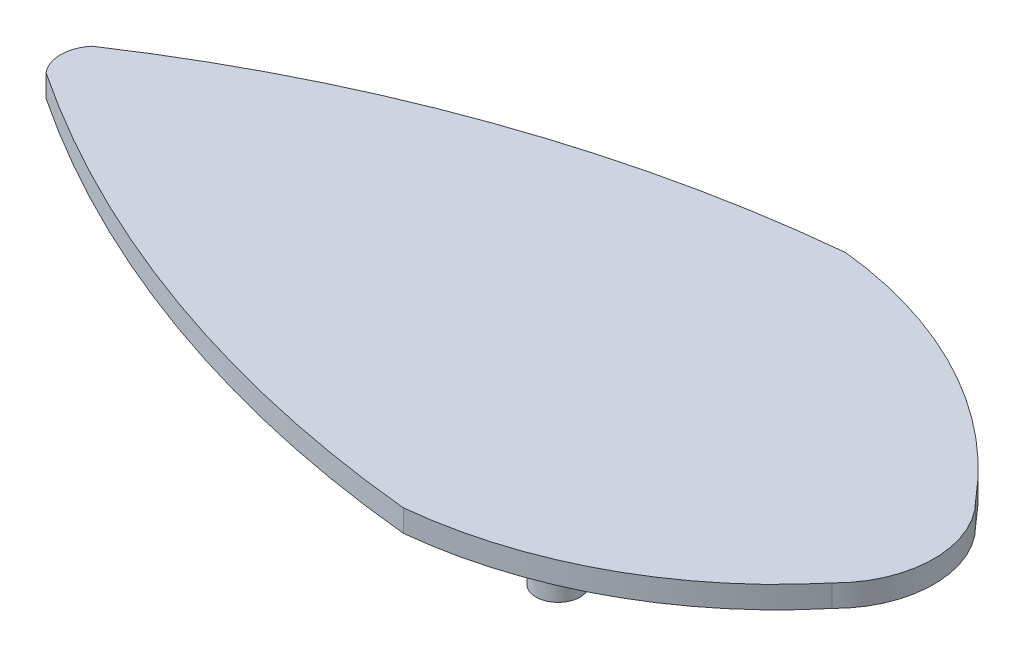
SolidWorks part; units mm, degrees
ref_plane "Alzado" through (0, 0, 0) normal (0, 0, 1) x (1, 0, 0)
ref_plane "Planta" through (0, 0, 0) normal (0, 1, 0) x (1, 0, 0)
ref_plane "Vista lateral" through (0, 0, 0) normal (1, 0, 0) x (0, 0, -1)
sketch "Croquis1" plane through (0, 0, 0) normal (0, 1, 0) x (1, 0, 0)
  line L0 (0, -63.5) -> (0, 63.5) construction
  line L1 (-161.925, 0) -> (88.9, 0) construction
  arc A0 (-159.5248, 6.6093) -> (0, 63.5) centre (34.1453, -284.3492) cw
  arc A1 (0, 63.5) -> (80.2701, 20.6208) centre (-12.4327, -56.3469) cw
  arc A2 (-159.5248, -6.6093) -> (0, -63.5) centre (34.1453, 284.3492) ccw
  arc A3 (0, -63.5) -> (80.2701, -20.6208) centre (-12.4327, 56.3469) ccw
  arc A4 (80.2701, 20.6208) -> (80.2701, -20.6208) centre (59.9486, 0) cw
  arc A5 (-159.5248, 6.6093) -> (-159.5248, -6.6093) centre (-151.625, 0) ccw
  point P3 (0, 0)
  point P12 (88.9, 0)
  point P14 (-161.925, 0)
  dimension "D1" = 127
  dimension "D2" = 250.825
  dimension "D3" = 88.9
extrude "Saliente-Extruir1" add sketch "Croquis1" along normal blind 6.35
sketch "Croquis2" plane through (0, 6.35, 0) normal (0, 1, 0) x (1, 0, 0)
  circle A0 centre (28.575, 47.625) radius 6.35
  circle A1 centre (28.575, -47.625) radius 6.35
  circle A2 centre (-136.525, 0) radius 6.35
  arc A3 (-159.5248, 6.6093) -> (-159.5248, -6.6093) centre (-151.625, 0) ccw construction
  point P9 (-161.925, 0)
  dimension "D1" = 25.4
  dimension "D2" = 95.25
  dimension "D3" = 47.625
  dimension "D4" = 165.1
extrude "Saliente-Extruir2" add sketch "Croquis2" against normal blind 6.35 from surface at -6.35 starting at face at (-25.1446, 0, 0)
